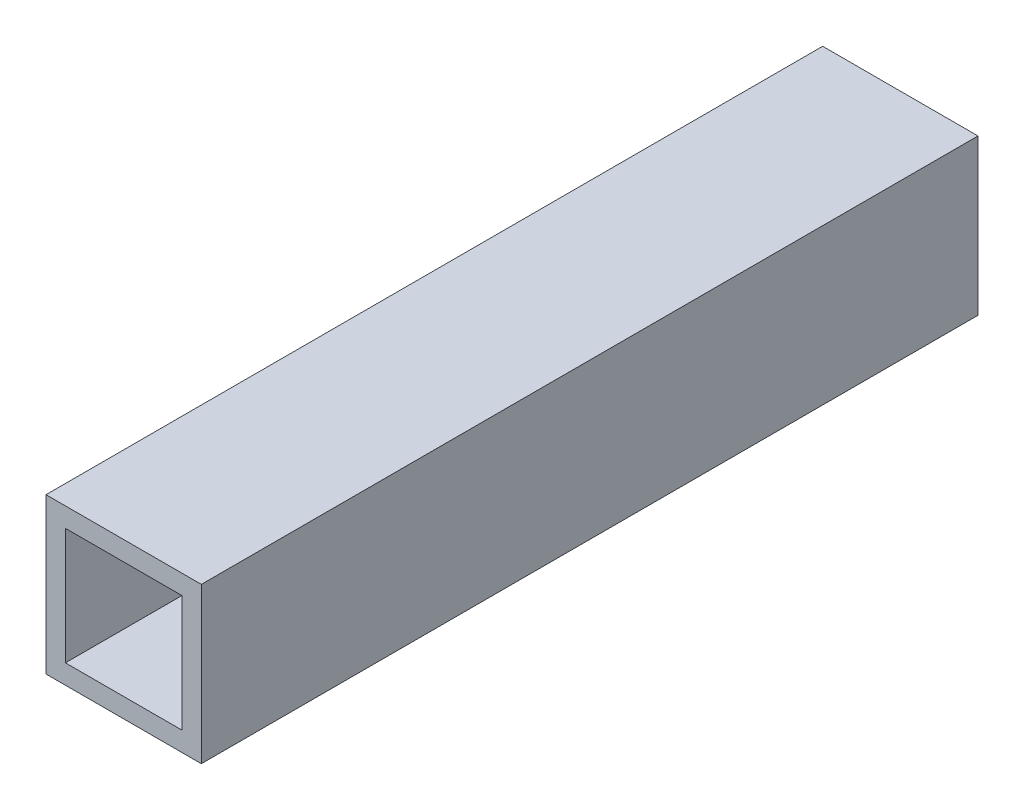
SolidWorks part; units mm, degrees
ref_plane "Front Plane" through (0, 0, 0) normal (0, 0, 1) x (1, 0, 0)
ref_plane "Top Plane" through (0, 0, 0) normal (0, 1, 0) x (1, 0, 0)
ref_plane "Right Plane" through (0, 0, 0) normal (1, 0, 0) x (0, 0, -1)
sketch "Sketch1" plane through (0, 0, 0) normal (0, 0, 1) x (1, 0, 0)
  line L1 (0, 0) -> (-25.4, 0)
  line L2 (0, 0) -> (0, 25.4)
  line L3 (0, 25.4) -> (-25.4, 25.4)
  line L4 (-25.4, 0) -> (-25.4, 25.4)
  dimension "D1" = 25.4
  dimension "D2" = 25.4
extrude "Boss-Extrude1" add sketch "Sketch1" along normal blind 127
sketch "Sketch2" plane through (0, 0, 127) normal (0, 0, 1) x (1, 0, 0)
  line L8 (0, 25.4) -> (-25.4, 25.4) construction
  line L9 (-22.225, 22.225) -> (-3.175, 22.225)
  line L10 (-22.225, 22.225) -> (-22.225, 3.175)
  line L11 (-22.225, 3.175) -> (-3.175, 3.175)
  line L12 (-3.175, 22.225) -> (-3.175, 3.175)
  line L14 (0, 0) -> (0, 25.4) construction
  dimension "D1" = 3.175
  dimension "D2" = 19.05
  dimension "D3" = 3.175
  dimension "D4" = 19.05
extrude "Cut-Extrude1" cut sketch "Sketch2" against normal through all
